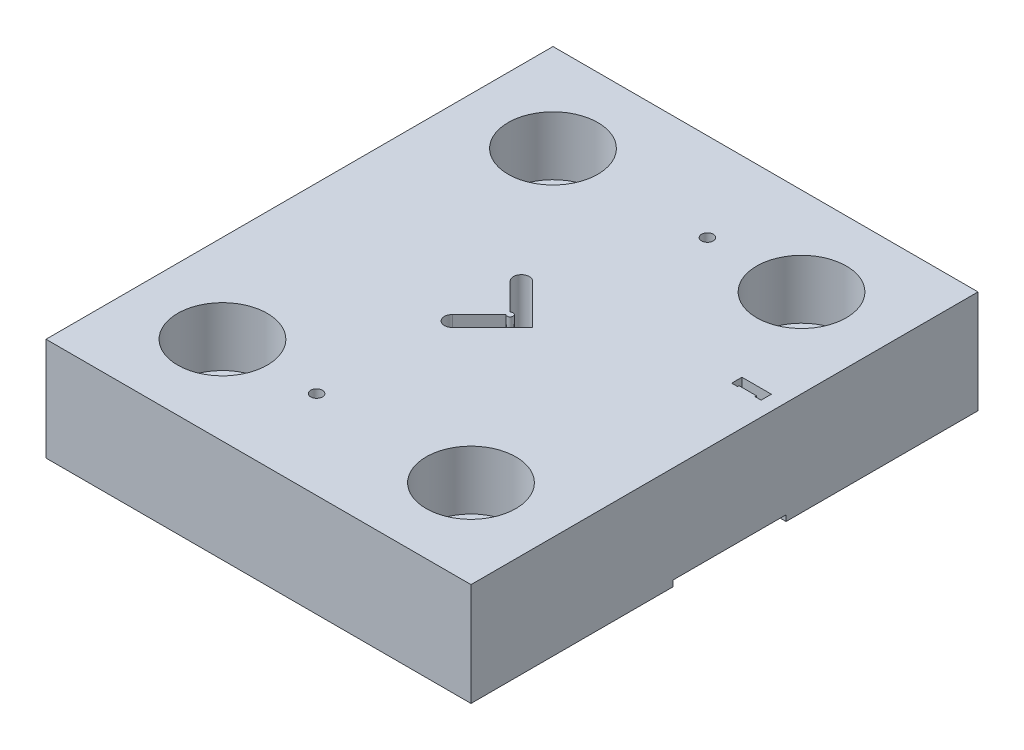
SolidWorks part; units mm, degrees
ref_plane "Front Plane" through (0, 0, 0) normal (0, 0, 1) x (1, 0, 0)
ref_plane "Top Plane" through (0, 0, 0) normal (0, 1, 0) x (1, 0, 0)
ref_plane "Right Plane" through (0, 0, 0) normal (1, 0, 0) x (0, 0, -1)
sketch "Sketch1" plane through (0, 0, 0) normal (0, 1, 0) x (1, 0, 0)
  line L1 (-72.25, -86.19) -> (72.25, -86.19)
  line L2 (-72.25, -86.19) -> (-72.25, 86.19)
  line L3 (-72.25, 86.19) -> (72.25, 86.19)
  line L4 (72.25, -86.19) -> (72.25, 86.19)
  line L5 (-72.25, -86.19) -> (72.25, 86.19) construction
  line L6 (-72.25, 86.19) -> (72.25, -86.19) construction
  point P0 (0, 0)
  dimension "D1" = 144.5
  dimension "D2" = 172.38
extrude "Boss-Extrude1" add sketch "Sketch1" along normal blind 35
sketch "Sketch2" plane through (0, 0, 0) normal (0, -1, 0) x (1, 0, 0)
  line L6 (-1.3339, -0.7071) -> (-10.4555, -9.8288)
  line L7 (-10.4555, 9.8288) -> (-1.3339, 0.7071)
  line L8 (7.01, 0) -> (-6.6372, 13.6472)
  line L9 (57.25, -20.94) -> (67.25, -20.94)
  line L10 (57.25, -17.44) -> (57.25, -20.94)
  line L11 (59.25, -17.44) -> (57.25, -17.44)
  line L12 (59.25, -17.94) -> (59.25, -17.44)
  line L13 (65.25, -17.94) -> (59.25, -17.94)
  line L14 (65.25, -17.44) -> (65.25, -17.94)
  line L15 (67.25, -17.44) -> (65.25, -17.44)
  line L16 (67.25, -20.94) -> (67.25, -17.44)
  line L17 (57.25, -20.94) -> (67.25, -20.94)
  line L18 (57.25, -17.44) -> (57.25, -20.94)
  line L19 (59.25, -17.44) -> (57.25, -17.44)
  line L20 (59.25, -17.94) -> (59.25, -17.44)
  line L21 (65.25, -17.94) -> (59.25, -17.94)
  line L22 (65.25, -17.44) -> (65.25, -17.94)
  line L23 (67.25, -17.44) -> (65.25, -17.44)
  line L24 (67.25, -20.94) -> (67.25, -17.44)
  line L25 (-6.6372, -13.6472) -> (7.01, 0)
  line L26 (-1.3339, -0.7071) -> (-10.4555, -9.8288)
  line L27 (-10.4555, 9.8288) -> (-1.3339, 0.7071)
  line L28 (7.01, 0) -> (-6.6372, 13.6472)
  line L29 (-6.6372, -13.6472) -> (7.01, 0)
  circle A0 centre (10.25, -56.19) radius 1.99 construction
  circle A1 centre (-42.25, -56.19) radius 10.5 construction
  circle A2 centre (42.25, -56.19) radius 10.5 construction
  circle A3 centre (-42.25, 56.19) radius 10.5 construction
  circle A4 centre (-10.25, 56.19) radius 1.99 construction
  circle A5 centre (42.25, 56.19) radius 10.5 construction
  circle A6 centre (10.25, -56.19) radius 1.99
  circle A7 centre (-42.25, -56.19) radius 10.5
  circle A8 centre (42.25, -56.19) radius 10.5
  circle A9 centre (-42.25, 56.19) radius 10.5
  circle A10 centre (-10.25, 56.19) radius 1.99
  circle A11 centre (42.25, 56.19) radius 10.5
  arc A15 (-10.4555, -9.8288) -> (-6.6372, -13.6472) centre (-8.5463, -11.738) ccw
  arc A16 (-1.3339, -0.7071) -> (-1.3339, 0.7071) centre (-0.6268, 0) ccw
  arc A17 (-6.6372, 13.6472) -> (-10.4555, 9.8288) centre (-8.5463, 11.738) ccw
  arc A18 (-10.4555, -9.8288) -> (-6.6372, -13.6472) centre (-8.5463, -11.738) ccw
  arc A19 (-1.3339, -0.7071) -> (-1.3339, 0.7071) centre (-0.6268, 0) ccw
  arc A20 (-6.6372, 13.6472) -> (-10.4555, 9.8288) centre (-8.5463, 11.738) ccw
  dimension "D1" = 0
  dimension "D2" = 0
extrude "Cut-Extrude1" cut sketch "Sketch2" against normal up to next
sketch "Sketch3" plane through (0, 0, 0) normal (0, -1, 0) x (1, 0, 0)
  line L0 (-72.25, 17.44) -> (-72.25, -17.94) construction
  line L1 (-72.25, 17.44) -> (72.25, 17.44) construction
  line L2 (72.25, 17.44) -> (72.25, -19.6447) construction
  line L3 (72.25, -19.6447) -> (72.25, -20.94) construction
  line L4 (57.25, -20.94) -> (72.25, -20.94) construction
  line L5 (57.25, -17.94) -> (57.25, -20.94) construction
  line L6 (-72.25, -17.94) -> (57.25, -17.94) construction
  line L7 (-72.25, 17.44) -> (-72.25, -17.94)
  line L8 (-72.25, 17.44) -> (72.25, 17.44)
  line L9 (72.25, 17.44) -> (72.25, -19.6447)
  line L10 (72.25, -19.6447) -> (72.25, -20.94)
  line L11 (57.25, -20.94) -> (72.25, -20.94)
  line L12 (57.25, -17.94) -> (57.25, -20.94)
  line L13 (-72.25, -17.94) -> (57.25, -17.94)
extrude "Cut-Extrude2" cut sketch "Sketch3" against normal blind 2
sketch "Sketch4" plane through (0, 35, 0) normal (0, 1, 0) x (1, 0, 0)
  circle A0 centre (-42.25, 56.19) radius 15.25
  circle A1 centre (42.25, 56.19) radius 15.25
  circle A2 centre (42.25, -56.19) radius 15.25
  circle A3 centre (-42.25, -56.19) radius 15.25
  dimension "D1" = 30.5
  dimension "D2" = 30.5
  dimension "D3" = 30.5
  dimension "D4" = 30.5
extrude "Cut-Extrude3" cut sketch "Sketch4" against normal blind 20
